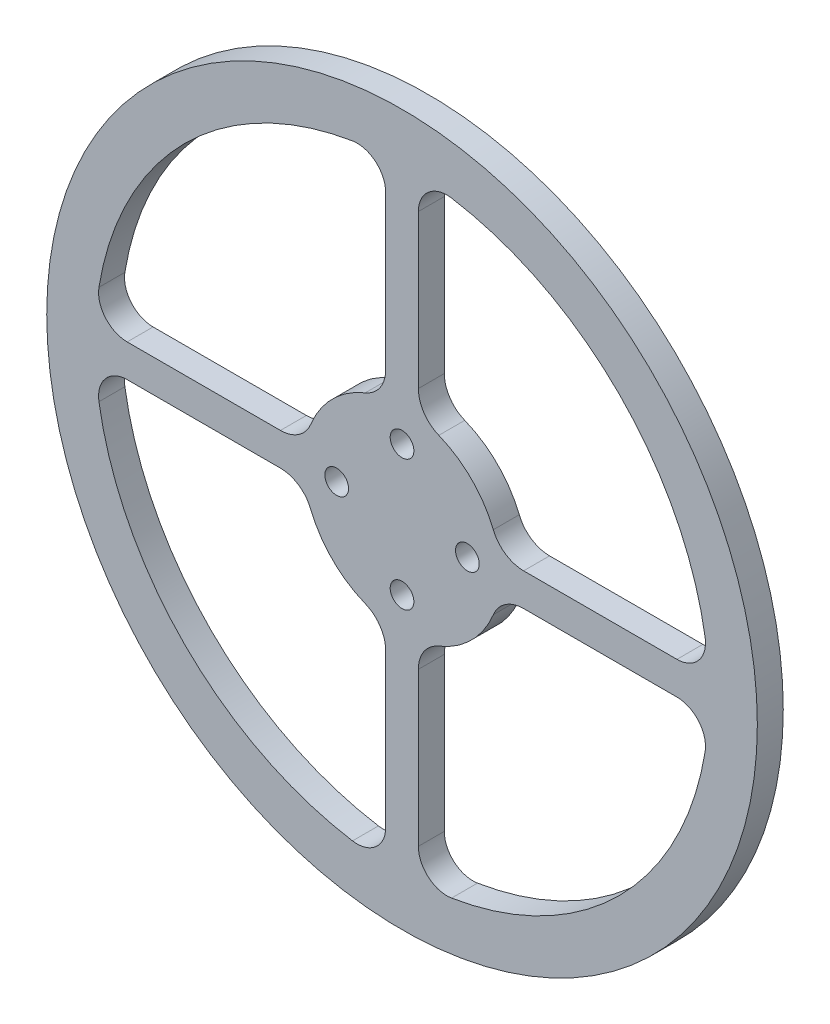
SolidWorks part; units mm, degrees
material "PETG_SRD"
ref_plane "Front Plane" through (0, 0, 0) normal (0, 0, 1) x (1, 0, 0)
ref_plane "Top Plane" through (0, 0, 0) normal (0, 1, 0) x (1, 0, 0)
ref_plane "Right Plane" through (0, 0, 0) normal (1, 0, 0) x (0, 0, -1)
sketch "Sketch1" plane through (0, 0, 0) normal (0, 0, 1) x (1, 0, 0)
  line L0 (0, 37.6) -> (0, -37.4) construction
  line L1 (-37.4, 0) -> (37.6, 0) construction
  line L2 (-37.5468, -2) -> (-11.8829, -2)
  line L3 (-2, 37.5468) -> (-2, 11.8829)
  line L4 (-37.5468, 2) -> (-11.8829, 2)
  line L5 (2, 37.5468) -> (2, 11.8829)
  line L6 (-37.4, 2) -> (37.6, 2) construction
  line L7 (-37.4, -2) -> (37.6, -2) construction
  line L8 (-2, 37.6) -> (-2, -37.4) construction
  line L9 (2, 37.6) -> (2, -37.4) construction
  line L10 (-2, -11.8829) -> (-2, -37.5468)
  line L11 (11.8829, -2) -> (37.5468, -2)
  line L12 (2, -11.8829) -> (2, -37.5468)
  line L13 (11.8829, 2) -> (37.5468, 2)
  circle A0 centre (0, 0) radius 43.5
  circle A1 centre (0, 8) radius 1.45
  circle A2 centre (0, -8) radius 1.45
  circle A3 centre (8, 0) radius 1.45
  circle A4 centre (-8, 0) radius 1.45
  circle A5 centre (0, 0) radius 8 construction
  arc A23 (-37.5468, -2) -> (-2, -37.5468) centre (0, 0) ccw
  arc A24 (2, -37.5468) -> (37.5468, -2) centre (0, 0) ccw
  arc A25 (37.5468, 2) -> (2, 37.5468) centre (0, 0) ccw
  arc A26 (-2, 37.5468) -> (-37.5468, 2) centre (0, 0) ccw
  arc A27 (-11.8829, -2) -> (-2, -11.8829) centre (0, 0) ccw
  arc A28 (-2, 11.8829) -> (-11.8829, 2) centre (0, 0) ccw
  arc A29 (11.8829, 2) -> (2, 11.8829) centre (0, 0) ccw
  arc A30 (2, -11.8829) -> (11.8829, -2) centre (0, 0) ccw
  dimension "D1" = 2.9
  dimension "D2" = 16
  dimension "D3" = 87
  dimension "D4" = 5.9
  dimension "D7" = 4.05
  dimension "D5" = 2
  dimension "D6" = 2
extrude "Boss-Extrude1" add sketch "Sketch1" along normal blind 3.175
ref_plane "Plane5" through (0, 0, -3.175) normal (0, 0, 1) x (1, 0, 0)
fillet "Fillet1" radius 4 8 edges at (2, 11.8829, 1.5875) (11.8829, 2, 1.5875) (11.8829, -2, 1.5875) (2, -11.8829, 1.5875) (-2, -11.8829, 1.5875) (-11.8829, 2, 1.5875) (-2, 11.8829, 1.5875) (-11.8829, -2, 1.5875)
fillet "Fillet2" radius 3.5 8 edges at (2, -37.5468, 1.5875) (-2, -37.5468, 1.5875) (37.5468, -2, 1.5875) (37.5468, 2, 1.5875) (2, 37.5468, 1.5875) (-2, 37.5468, 1.5875) (-37.5468, 2, 1.5875) (-37.5468, -2, 1.5875)
sketch "Sketch3" plane through (0, 0, 0) normal (0, 0, -1) x (-1, 0, 0)
  circle A0 centre (0, 0) radius 3.225
  dimension "D1" = 6.45
extrude "Boss-Extrude2" add sketch "Sketch3" along normal up to surface (3.175 mm away) up to plane "Plane5"
equation "\"Rim\"= 5.9"
equation "\"D4@Sketch1\"=\"Rim\""
equation "\"`.14\"=1.5"
